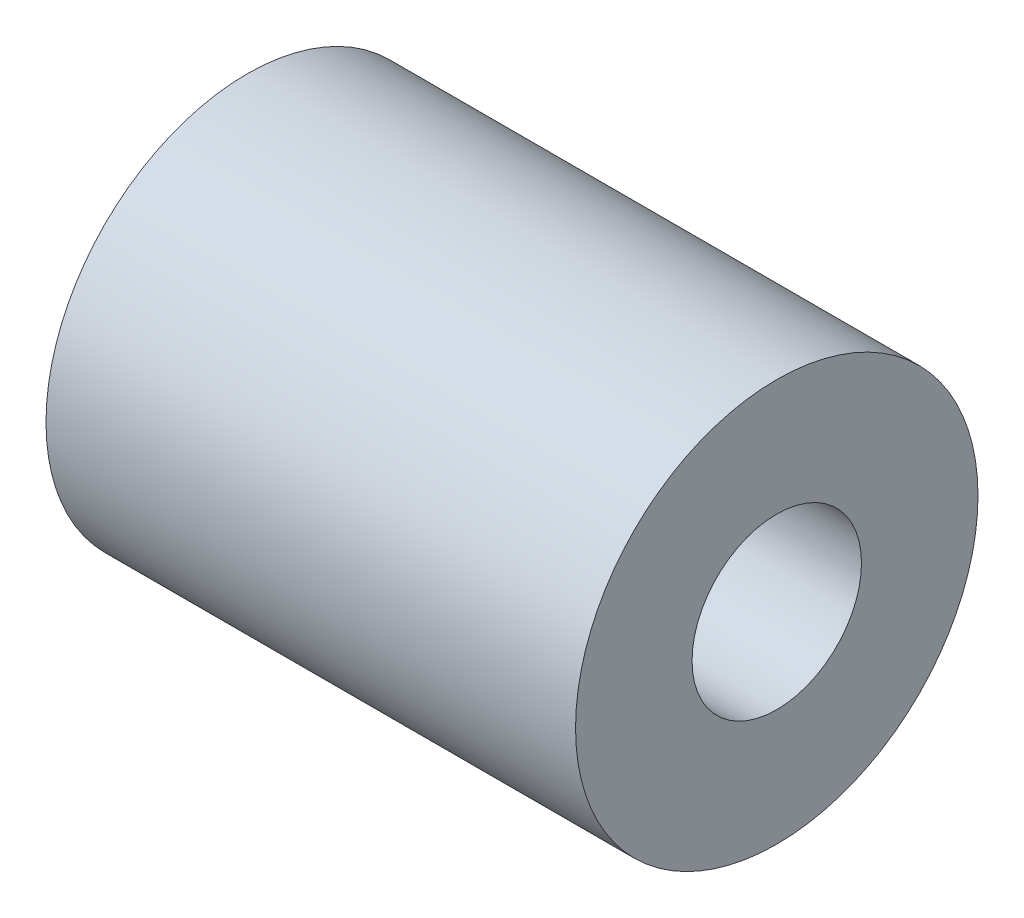
SolidWorks part; units mm, degrees
material "6061 Alloy"
ref_plane "Front Plane" through (0, 0, 0) normal (0, 0, 1) x (1, 0, 0)
ref_plane "Top Plane" through (0, 0, 0) normal (0, 1, 0) x (1, 0, 0)
ref_plane "Right Plane" through (0, 0, 0) normal (1, 0, 0) x (0, 0, -1)
sketch "Sketch1" plane through (0, 0, 0) normal (0, 1, 0) x (1, 0, 0)
  line L0 (0, 0) -> (12.6216, 0) construction
  line L1 (-6.2838, 2.5) -> (6.2162, 2.5)
  line L2 (6.2162, 2.5) -> (6.2162, 4)
  line L3 (6.2162, 4) -> (18.7162, 4)
  line L4 (18.7162, 4) -> (18.7162, 9.5)
  line L5 (18.7162, 9.5) -> (-6.2838, 9.5)
  line L6 (-6.2838, 9.5) -> (-6.2838, 2.5)
  point P9 (6.2162, 3.25)
  dimension "D1" = 2.5
  dimension "D2" = 4
  dimension "D3" = 9.5
  dimension "D4" = 25
  dimension "D5" = 12.5
revolve "Revolve1" add sketch "Sketch1" angle 360 about L0
